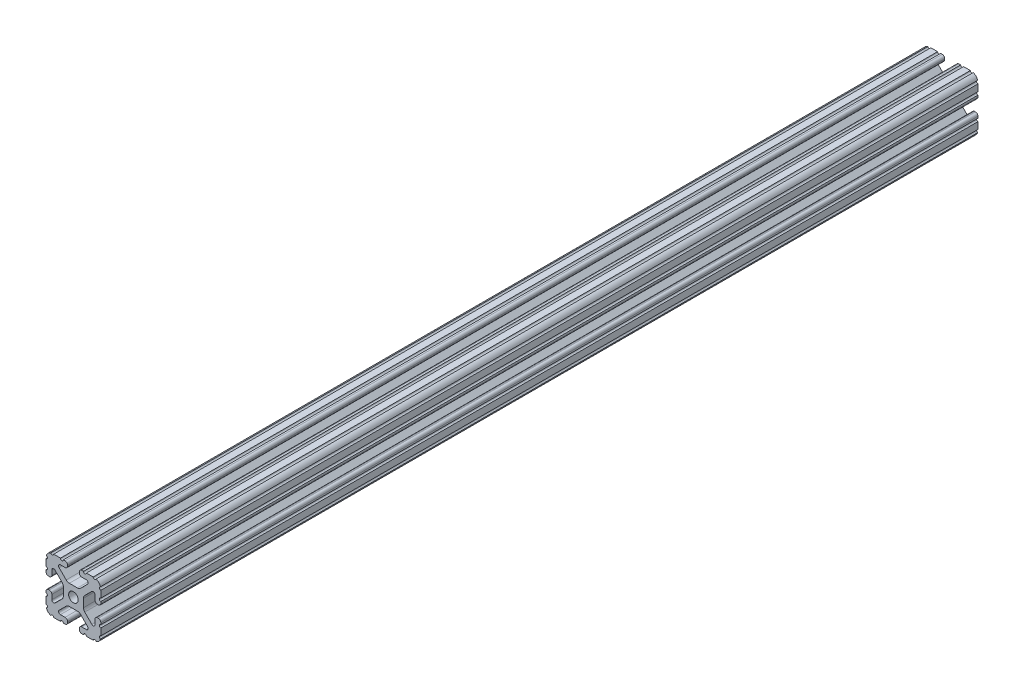
SolidWorks part; units mm, degrees
ref_plane "Front Plane" through (0, 0, 0) normal (0, 0, 1) x (1, 0, 0)
ref_plane "Top Plane" through (0, 0, 0) normal (0, 1, 0) x (1, 0, 0)
ref_plane "Right Plane" through (0, 0, 0) normal (1, 0, 0) x (0, 0, -1)
sketch "Sketch2" plane through (0, 0, 0) normal (0, 0, 1) x (1, 0, 0)
  line L0 (0, 19.05) -> (0, -19.05) construction
  line L1 (-19.05, 0) -> (19.05, 0) construction
  line L2 (4.064, -19.05) -> (19.05, -19.05)
  line L3 (19.05, -19.05) -> (19.05, -4.064)
  line L4 (4.064, -19.05) -> (4.064, -14.986)
  line L5 (4.064, -14.986) -> (12.1123, -14.986)
  line L6 (12.1123, -14.986) -> (4.1113, -6.985)
  line L7 (0, 0) -> (19.05, -19.05) construction
  line L8 (19.05, -4.064) -> (14.986, -4.064)
  line L9 (14.986, -4.064) -> (14.986, -12.1123)
  line L10 (14.986, -12.1123) -> (6.985, -4.1113)
  circle A0 centre (0, 0) radius 3.3274
  arc A1 (8.9963, -14.986) -> (9.909, -12.7826) centre (8.9963, -13.6953) ccw construction
  point P8 (0, -6.985)
  dimension "Center Hole Diameter" = 6.6548
  dimension "Rail Height" = 38.1
  dimension "Rail Width" = 38.1
  dimension "T-Slot Width" = 8.128
  dimension "Slot Inner Width" = 20.574
  dimension "Thickness" = 4.064
  dimension "Slot Depth" = 8.001
  dimension "D1" = 4.064
sketch "Sketch3" plane through (0, 0, 0) normal (1, 0, 0) x (0, 0, -1)
  line L0 (-152.4, -19.05) -> (152.4, -19.05) construction
  line L1 (-127, 0) -> (127, 0) construction
  dimension "Length" = 304.8
  dimension "D1" = 25.4
sketch "Sketch4" plane through (0, 0, 0) normal (0, 0, 1) x (1, 0, 0)
  line L0 (5.7912, -19.05) -> (14.3002, -19.05)
  line L1 (4.064, -19.05) -> (19.05, -19.05) construction
  line L2 (4.064, -19.05) -> (4.064, -14.986) construction
  line L3 (4.064, -14.986) -> (12.1123, -14.986) construction
  line L4 (4.064, -16.7132) -> (4.064, -17.3228)
  line L5 (5.7912, -14.986) -> (8.9963, -14.986)
  line L6 (0, -6.985) -> (2.833, -6.985)
  line L7 (12.1123, -14.986) -> (4.1113, -6.985) construction
  line L8 (5.0152, -7.8889) -> (9.909, -12.7826)
  line L9 (19.05, -19.05) -> (19.05, -4.064) construction
  line L10 (14.986, -12.1123) -> (6.985, -4.1113) construction
  line L11 (14.986, -4.064) -> (14.986, -12.1123) construction
  line L12 (14.986, -8.9963) -> (14.986, -5.7912)
  line L13 (19.05, -4.064) -> (14.986, -4.064) construction
  line L14 (16.7132, -4.064) -> (17.3228, -4.064)
  line L15 (19.05, -5.7912) -> (19.05, -14.3002)
  line L16 (12.7826, -9.909) -> (7.8889, -5.0152)
  line L17 (6.985, 0) -> (6.985, -2.833)
  line L18 (-19.05, 0) -> (19.05, 0) construction
  line L19 (0, -6.985) -> (0, -3.3274)
  line L20 (0, 19.05) -> (0, -19.05) construction
  line L21 (6.985, 0) -> (3.3274, 0)
  arc A0 (4.064, -17.3228) -> (5.7912, -19.05) centre (5.7912, -17.3228) ccw
  arc A2 (4.064, -16.7132) -> (5.7912, -14.986) centre (5.7912, -16.7132) cw
  arc A3 (8.9963, -14.986) -> (9.909, -12.7826) centre (8.9963, -13.6953) ccw
  arc A4 (2.833, -6.985) -> (5.0152, -7.8889) centre (2.833, -10.0711) cw
  arc A5 (14.3002, -19.05) -> (19.05, -14.3002) centre (14.3002, -14.3002) ccw
  arc A6 (12.7826, -9.909) -> (14.986, -8.9963) centre (13.6953, -8.9963) ccw
  arc A7 (14.986, -5.7912) -> (16.7132, -4.064) centre (16.7132, -5.7912) cw
  arc A8 (17.3228, -4.064) -> (19.05, -5.7912) centre (17.3228, -5.7912) cw
  arc A9 (7.8889, -5.0152) -> (6.985, -2.833) centre (10.0711, -2.833) cw
  circle A10 centre (0, 0) radius 3.3274 construction
  arc A11 (0, -3.3274) -> (3.3274, 0) centre (0, 0) ccw
  dimension "D1" = 4.7498
  dimension "D2" = 3.0861
  dimension "D3" = 1.7272
extrude "Boss-Extrude1" add sketch "Sketch4" along normal mid plane 609.6
sketch "Sketch5" plane through (0, 0, 0) normal (0, 0, 1) x (1, 0, 0)
  line L0 (4.064, -19.05) -> (19.05, -19.05) construction
  line L1 (5.7912, -14.986) -> (8.9963, -14.986) construction
  line L3 (0, 0) -> (19.05, -19.05) construction
  line L4 (8.9963, -14.986) -> (8.9963, -19.05) construction
  line L5 (12.1123, -14.986) -> (4.1113, -6.985) construction
  circle A0 centre (14.7395, -19.05) radius 1.016
  circle A1 centre (7.9803, -19.05) radius 1.016
  circle A2 centre (19.05, -14.7395) radius 1.016
  circle A3 centre (19.05, -7.9803) radius 1.016
  point P10 (7.3938, -14.986)
  point P12 (13.6953, -8.9963)
extrude "Cut-Extrude1" cut sketch "Sketch5" against normal through all both and the other way through all
mirror "Mirror1" about plane through (0, 0, 0) normal (1, 0, 0) of bodies 137 134
mirror "Mirror2" about plane through (0, 0, 0) normal (0, 1, 0) of bodies 135
equation "\"D1@Boss-Extrude1\"=\"Length@Sketch3\""
equation "\"D1@Sketch2\"=\"Thickness@Sketch2\""
equation "\"D2@Sketch4\"=\"Slot Inner Width@Sketch2\"*0.15"
equation "\"D1@Sketch4\"=\"D3@Sketch4\"*2.75"
equation "\"D3@Sketch4\"=\"Thickness@Sketch2\"*0.425"
equation "\"D1@Sketch5\"=\"Thickness@Sketch2\"*0.5"
